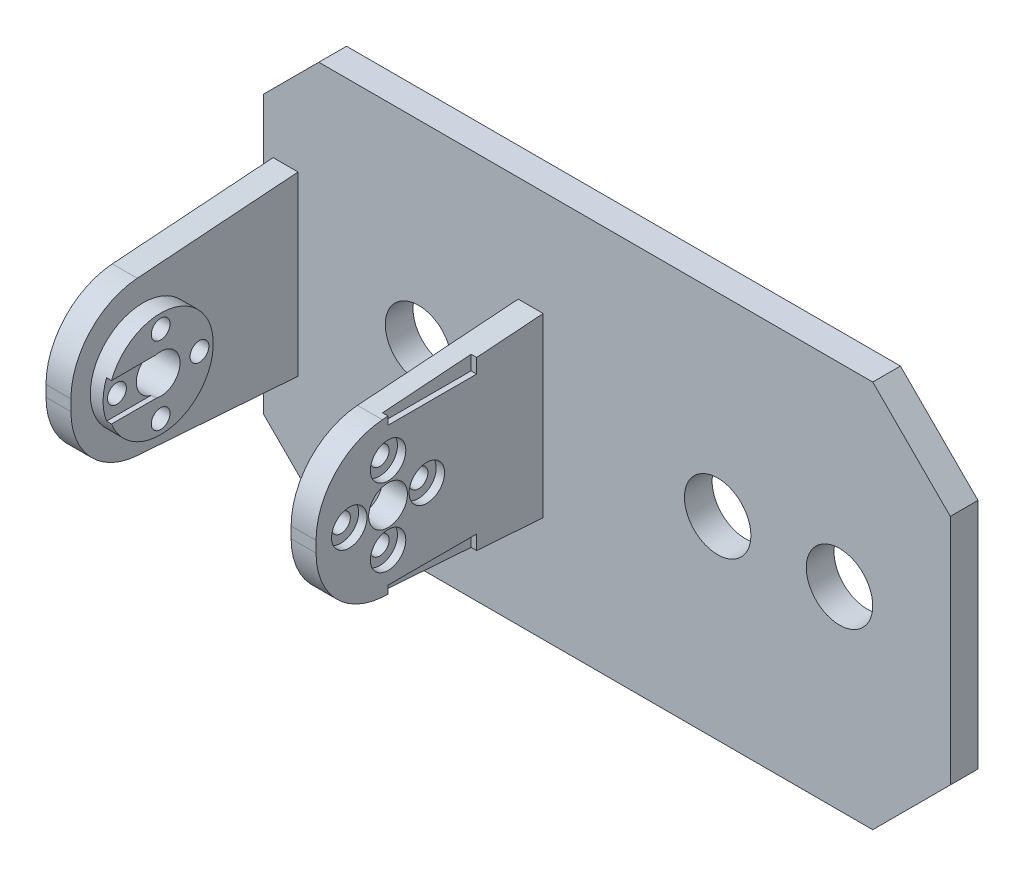
SolidWorks part; units mm, degrees
ref_plane "Front Plane" through (0, 0, 0) normal (0, 0, 1) x (1, 0, 0)
ref_plane "Top Plane" through (0, 0, 0) normal (0, 1, 0) x (1, 0, 0)
ref_plane "Right Plane" through (0, 0, 0) normal (1, 0, 0) x (0, 0, -1)
ref_plane "PZ_m33_000" through (0, 0, -33) normal (0, 0, 1) x (1, 0, 0)
sketch "S_prism1" plane through (0, 0, -33) normal (0, 0, 1) x (1, 0, 0)
  line L0 (56, -21) -> (56, 21)
  line L1 (56, 21) -> (42, 35)
  line L2 (42, 35) -> (-58, 35)
  line L3 (-58, 35) -> (-68, 25)
  line L4 (-68, 25) -> (-68, -25)
  line L5 (-68, -25) -> (-58, -35)
  line L6 (-58, -35) -> (42, -35)
  line L7 (42, -35) -> (56, -21)
extrude "Boss_1" add sketch "S_prism1" along normal blind 5
ref_plane "PX_m22_000" through (-22, 0, 0) normal (1, 0, 0) x (0, 0, -1)
sketch "S_prism2" plane through (-22, 0, 0) normal (1, 0, 0) x (0, 0, -1)
  line L0 (28.5, -16) -> (28.5, 16)
  line L1 (28.5, 16) -> (-1.0301, 13.8653)
  line L2 (-13, 0.9989) -> (-13, -0.9989)
  line L3 (-1.0301, -13.8653) -> (28.5, -16)
  arc A0 (-1.0301, 13.8653) -> (-13, 0.9989) centre (-0.1001, 0.999) ccw
  arc A1 (-13, -0.9989) -> (-1.0301, -13.8653) centre (-0.1001, -0.999) ccw
extrude "Boss_2" add sketch "S_prism2" along normal blind 4.5
ref_plane "PX_m61_750" through (-61.75, 0, 0) normal (1, 0, 0) x (0, 0, -1)
sketch "S_cyl3" plane through (-61.75, 0, 0) normal (1, 0, 0) x (0, 0, -1)
  circle A0 centre (0, 0) radius 9.5
  dimension "D1_S_cyl3" = 19
extrude "Boss_3" add sketch "S_cyl3" along normal blind 3.2
ref_plane "PX_m66_250" through (-66.25, 0, 0) normal (1, 0, 0) x (0, 0, -1)
sketch "S_prism4" plane through (-66.25, 0, 0) normal (1, 0, 0) x (0, 0, -1)
  line L0 (28.5, -16) -> (28.5, 16)
  line L1 (28.5, 16) -> (-1.0301, 13.8653)
  line L2 (-13, 0.9989) -> (-13, -0.9989)
  line L3 (-1.0301, -13.8653) -> (28.5, -16)
  arc A0 (-1.0301, 13.8653) -> (-13, 0.9989) centre (-0.1001, 0.999) ccw
  arc A1 (-13, -0.9989) -> (-1.0301, -13.8653) centre (-0.1001, -0.999) ccw
extrude "Boss_4" add sketch "S_prism4" along normal blind 4.5
ref_plane "PX_m22_100" through (-22.1, 0, 0) normal (1, 0, 0) x (0, 0, -1)
sketch "S_hole5" plane through (-22.1, 0, 0) normal (1, 0, 0) x (0, 0, -1)
  circle A0 centre (0, 0) radius 3.5
  dimension "D1_S_hole5" = 7
extrude "Hole_5" cut sketch "S_hole5" along normal blind 4.7
sketch "S_hole6" plane through (-22.1, 0, 0) normal (1, 0, 0) x (0, 0, -1)
  circle A0 centre (0, 7) radius 1.7
  dimension "D1_S_hole6" = 3.4
  dimension "P2" = 7
extrude "Hole_6" cut sketch "S_hole6" along normal blind 4.7
sketch "S_hole7" plane through (-22.1, 0, 0) normal (1, 0, 0) x (0, 0, -1)
  circle A0 centre (-7, 0) radius 1.7
  dimension "D1_S_hole7" = 3.4
  dimension "P2" = 7
extrude "Hole_7" cut sketch "S_hole7" along normal blind 4.7
sketch "S_hole8" plane through (-22.1, 0, 0) normal (1, 0, 0) x (0, 0, -1)
  circle A0 centre (0, -7) radius 1.7
  dimension "D1_S_hole8" = 3.4
  dimension "P2" = 7
extrude "Hole_8" cut sketch "S_hole8" along normal blind 4.7
sketch "S_hole9" plane through (-22.1, 0, 0) normal (1, 0, 0) x (0, 0, -1)
  circle A0 centre (7, 0) radius 1.7
  dimension "D1_S_hole9" = 3.4
  dimension "P2" = 7
extrude "Hole_9" cut sketch "S_hole9" along normal blind 4.7
ref_plane "PX_m19_000" through (-19, 0, 0) normal (1, 0, 0) x (0, 0, -1)
sketch "S_hole10" plane through (-19, 0, 0) normal (1, 0, 0) x (0, 0, -1)
  circle A0 centre (0, 7) radius 3.2
  dimension "D1_S_hole10" = 6.4
  dimension "P2" = 7
extrude "Hole_10" cut sketch "S_hole10" along normal blind 1.6
sketch "S_hole11" plane through (-19, 0, 0) normal (1, 0, 0) x (0, 0, -1)
  circle A0 centre (-7, 0) radius 3.2
  dimension "D1_S_hole11" = 6.4
  dimension "P2" = 7
extrude "Hole_11" cut sketch "S_hole11" along normal blind 1.6
sketch "S_hole12" plane through (-19, 0, 0) normal (1, 0, 0) x (0, 0, -1)
  circle A0 centre (0, -7) radius 3.2
  dimension "D1_S_hole12" = 6.4
  dimension "P2" = 7
extrude "Hole_12" cut sketch "S_hole12" along normal blind 1.6
sketch "S_hole13" plane through (-19, 0, 0) normal (1, 0, 0) x (0, 0, -1)
  circle A0 centre (7, 0) radius 3.2
  dimension "D1_S_hole13" = 6.4
  dimension "P2" = 7
extrude "Hole_13" cut sketch "S_hole13" along normal blind 1.6
ref_plane "PX_m66_350" through (-66.35, 0, 0) normal (1, 0, 0) x (0, 0, -1)
sketch "S_hole14" plane through (-66.35, 0, 0) normal (1, 0, 0) x (0, 0, -1)
  circle A0 centre (0, 0) radius 3.5
  dimension "D1_S_hole14" = 7
extrude "Hole_14" cut sketch "S_hole14" along normal blind 7.9
sketch "S_hole15" plane through (-66.35, 0, 0) normal (1, 0, 0) x (0, 0, -1)
  circle A0 centre (0, 7) radius 1.7
  dimension "D1_S_hole15" = 3.4
  dimension "P2" = 7
extrude "Hole_15" cut sketch "S_hole15" along normal blind 7.9
sketch "S_hole16" plane through (-66.35, 0, 0) normal (1, 0, 0) x (0, 0, -1)
  circle A0 centre (-7, 0) radius 1.7
  dimension "D1_S_hole16" = 3.4
  dimension "P2" = 7
extrude "Hole_16" cut sketch "S_hole16" along normal blind 7.9
sketch "S_hole17" plane through (-66.35, 0, 0) normal (1, 0, 0) x (0, 0, -1)
  circle A0 centre (0, -7) radius 1.7
  dimension "D1_S_hole17" = 3.4
  dimension "P2" = 7
extrude "Hole_17" cut sketch "S_hole17" along normal blind 7.9
sketch "S_hole18" plane through (-66.35, 0, 0) normal (1, 0, 0) x (0, 0, -1)
  circle A0 centre (7, 0) radius 1.7
  dimension "D1_S_hole18" = 3.4
  dimension "P2" = 7
extrude "Hole_18" cut sketch "S_hole18" along normal blind 7.9
sketch "S_hole19" plane through (-66.35, 0, 0) normal (1, 0, 0) x (0, 0, -1)
  circle A0 centre (0, 7) radius 3.2
  dimension "D1_S_hole19" = 6.4
  dimension "P2" = 7
extrude "Hole_19" cut sketch "S_hole19" along normal blind 2.1
sketch "S_hole20" plane through (-66.35, 0, 0) normal (1, 0, 0) x (0, 0, -1)
  circle A0 centre (-7, 0) radius 3.2
  dimension "D1_S_hole20" = 6.4
  dimension "P2" = 7
extrude "Hole_20" cut sketch "S_hole20" along normal blind 2.1
sketch "S_hole21" plane through (-66.35, 0, 0) normal (1, 0, 0) x (0, 0, -1)
  circle A0 centre (0, -7) radius 3.2
  dimension "D1_S_hole21" = 6.4
  dimension "P2" = 7
extrude "Hole_21" cut sketch "S_hole21" along normal blind 2.1
sketch "S_hole22" plane through (-66.35, 0, 0) normal (1, 0, 0) x (0, 0, -1)
  circle A0 centre (7, 0) radius 3.2
  dimension "D1_S_hole22" = 6.4
  dimension "P2" = 7
extrude "Hole_22" cut sketch "S_hole22" along normal blind 2.1
sketch "S_cut23" plane through (0, 0, 0) normal (0, 0, 1) x (1, 0, 0)
  line L0 (-59.45, -3.4) -> (-58.45, -3.4)
  line L1 (-58.45, -3.4) -> (-58.45, 3.4)
  line L2 (-58.45, 3.4) -> (-59.45, 3.4)
  line L3 (-59.45, 3.4) -> (-59.45, -3.4)
  dimension "P1" = 59.45
  dimension "P2" = 3.4
  dimension "P3" = 58.45
  dimension "P4" = 3.4
  dimension "P5" = 58.45
  dimension "P6" = 3.4
  dimension "P7" = 59.45
  dimension "P8" = 3.4
extrude "Pocket_23" cut sketch "S_cut23" along normal blind 10
ref_plane "PZ_m33_100" through (0, 0, -33.1) normal (0, 0, 1) x (1, 0, 0)
sketch "S_hole24" plane through (0, 0, -33.1) normal (0, 0, 1) x (1, 0, 0)
  circle A0 centre (-40, 0) radius 6
  dimension "D1_S_hole24" = 12
  dimension "P2" = 40
extrude "Hole_24" cut sketch "S_hole24" along normal blind 5.2
sketch "S_hole25" plane through (0, 0, -33.1) normal (0, 0, 1) x (1, 0, 0)
  circle A0 centre (14, 0) radius 6
  dimension "D1_S_hole25" = 12
  dimension "P2" = 14
extrude "Hole_25" cut sketch "S_hole25" along normal blind 5.2
sketch "S_hole26" plane through (0, 0, -33.1) normal (0, 0, 1) x (1, 0, 0)
  circle A0 centre (36, 0) radius 6
  dimension "D1_S_hole26" = 12
  dimension "P2" = 36
extrude "Hole_26" cut sketch "S_hole26" along normal blind 5.2
ref_plane "PZ_m16_000" through (0, 0, -16) normal (0, 0, 1) x (1, 0, 0)
sketch "S_cut27" plane through (0, 0, -16) normal (0, 0, 1) x (1, 0, 0)
  line L0 (-18.5, 12.5) -> (-17.4, 12.5)
  line L1 (-17.4, 12.5) -> (-17.4, 17)
  line L2 (-17.4, 17) -> (-18.5, 17)
  line L3 (-18.5, 17) -> (-18.5, 12.5)
  dimension "P1" = 18.5
  dimension "P2" = 12.5
  dimension "P3" = 17.4
  dimension "P4" = 12.5
  dimension "P5" = 17.4
  dimension "P6" = 17
  dimension "P7" = 18.5
  dimension "P8" = 17
extrude "Pocket_27" cut sketch "S_cut27" along normal blind 16
sketch "S_cut28" plane through (0, 0, -16) normal (0, 0, 1) x (1, 0, 0)
  line L0 (-18.5, -17) -> (-17.4, -17)
  line L1 (-17.4, -17) -> (-17.4, -12.5)
  line L2 (-17.4, -12.5) -> (-18.5, -12.5)
  line L3 (-18.5, -12.5) -> (-18.5, -17)
  dimension "P1" = 18.5
  dimension "P2" = 17
  dimension "P3" = 17.4
  dimension "P4" = 17
  dimension "P5" = 17.4
  dimension "P6" = 12.5
  dimension "P7" = 18.5
  dimension "P8" = 12.5
extrude "Pocket_28" cut sketch "S_cut28" along normal blind 16
equation "\"plate_t\" = 3"
equation "\"clearance\" = 0.5"
